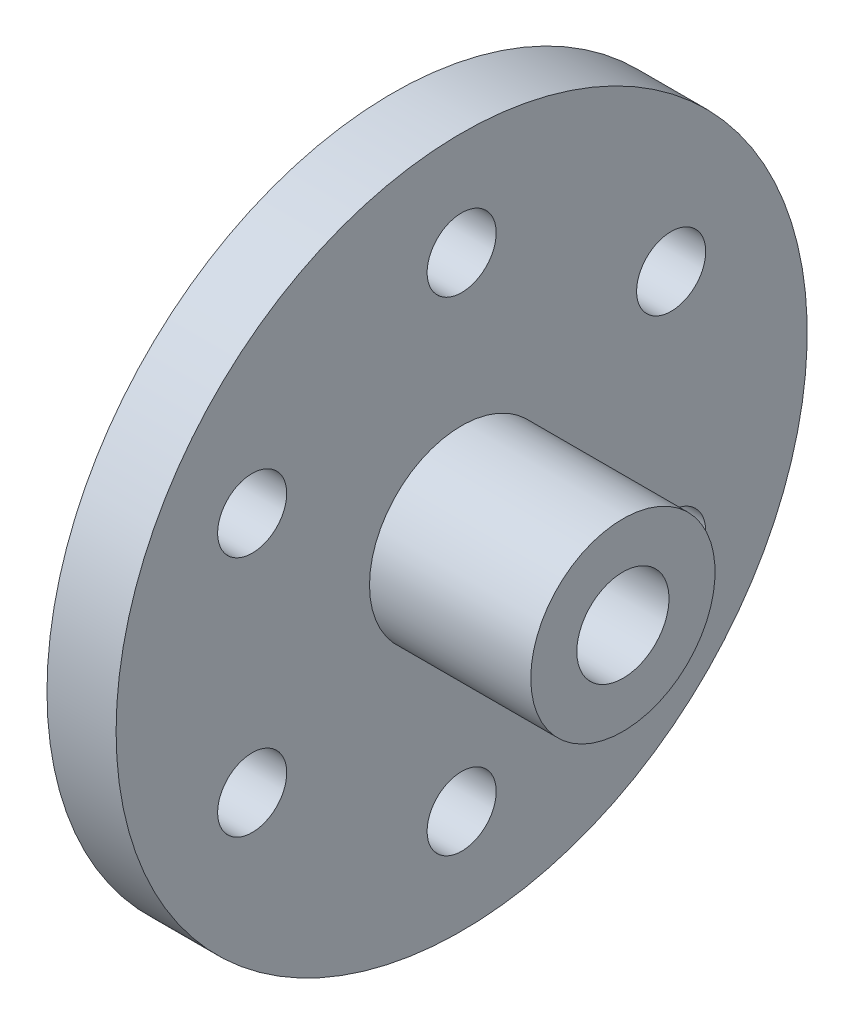
SolidWorks part; units mm, degrees
ref_plane "Front Plane" through (0, 0, 0) normal (0, 0, 1) x (1, 0, 0)
ref_plane "Top Plane" through (0, 0, 0) normal (0, 1, 0) x (1, 0, 0)
ref_plane "Right Plane" through (0, 0, 0) normal (1, 0, 0) x (0, 0, -1)
sketch "Sketch1" plane through (0, 0, 0) normal (0, 0, 1) x (1, 0, 0)
  line L0 (0, 0) -> (9, 0) construction
  line L4 (10, 4) -> (3, 4)
  line L5 (3, 4) -> (3, 15)
  line L6 (3, 15) -> (0, 15)
  line L7 (0, 15) -> (0, 2)
  line L9 (0, 2) -> (10, 2)
  line L10 (10, 2) -> (10, 4)
  dimension "D1" = 3
  dimension "D2" = 7
  dimension "D3" = 15
  dimension "D4" = 4
  dimension "D8" = 9
  dimension "D11" = 2
revolve "Revolve1" add sketch "Sketch1" angle 360 about L0
sketch "Sketch2" plane through (0, 0, 0) normal (-1, 0, 0) x (0, 0, 1)
  line L0 (0, 0) -> (0, 10.5) construction
  circle A0 centre (0, 10.5) radius 1.5
  circle A4 centre (9.0933, 5.25) radius 1.5
  circle A5 centre (9.0933, -5.25) radius 1.5
  circle A6 centre (0, -10.5) radius 1.5
  circle A7 centre (-9.0933, -5.25) radius 1.5
  circle A8 centre (-9.0933, 5.25) radius 1.5
  point P13 (0, 0)
  point P17 (0, 0)
  dimension "D1" = 3
  dimension "D2" = 10.5
  dimension "D3" = 6
extrude "Cut-Extrude5" cut sketch "Sketch2" against normal through all
